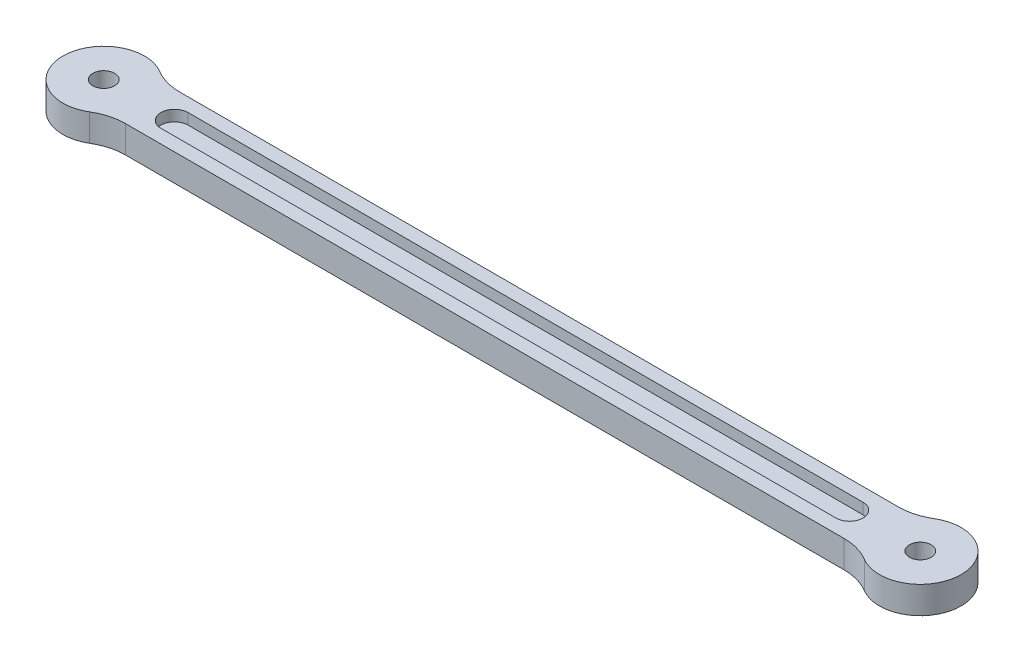
SolidWorks part; units mm, degrees
ref_plane "Front Plane" through (0, 0, 0) normal (0, 0, 1) x (1, 0, 0)
ref_plane "Top Plane" through (0, 0, 0) normal (0, 1, 0) x (1, 0, 0)
ref_plane "Right Plane" through (0, 0, 0) normal (1, 0, 0) x (0, 0, -1)
sketch "Sketch1" plane through (0, 0, 0) normal (0, 1, 0) x (1, 0, 0)
  line L0 (-85.2809, 7.177) -> (79.7191, 7.177) construction
  line L4 (-68.767, 12.177) -> (63.2052, 12.177)
  line L5 (-68.767, 2.177) -> (63.2052, 2.177)
  circle A0 centre (-77.7809, 7.177) radius 2
  arc A1 (-73.9178, 13.6055) -> (-73.9178, 0.7484) centre (-77.7809, 7.177) ccw
  circle A2 centre (72.2191, 7.177) radius 2
  arc A3 (68.356, 0.7484) -> (68.356, 13.6055) centre (72.2191, 7.177) ccw
  arc A4 (63.2052, 2.177) -> (68.356, 0.7484) centre (63.2052, -7.823) cw
  arc A5 (63.2052, 12.177) -> (68.356, 13.6055) centre (63.2052, 22.177) ccw
  arc A6 (-68.767, 2.177) -> (-73.9178, 0.7484) centre (-68.767, -7.823) ccw
  arc A7 (-68.767, 12.177) -> (-73.9178, 13.6055) centre (-68.767, 22.177) cw
  point P2 (66.6289, 2.177)
  point P15 (66.6289, 12.177)
  point P18 (-72.1907, 2.177)
  point P21 (-72.1907, 12.177)
  dimension "D3" = 4
  dimension "D5" = 4
  dimension "D2" = 10
  dimension "D1" = 5
  dimension "D4" = 7.5
  dimension "D6" = 7.5
  dimension "D7" = 150
extrude "Boss-Extrude1" add sketch "Sketch1" along normal blind 5
sketch "Sketch3" plane through (0, 5, 0) normal (0, 1, 0) x (1, 0, 0)
  line L1 (-64.7809, 9.677) -> (59.2191, 9.677)
  line L2 (-64.7809, 4.677) -> (59.2191, 4.677)
  arc A2 (-64.7809, 9.677) -> (-64.7809, 4.677) centre (-64.7809, 7.177) ccw
  arc A3 (59.2191, 4.677) -> (59.2191, 9.677) centre (59.2191, 7.177) ccw
  dimension "D1" = 5
  dimension "D3" = 5
extrude "Cut-Extrude1" cut sketch "Sketch3" against normal blind 2
